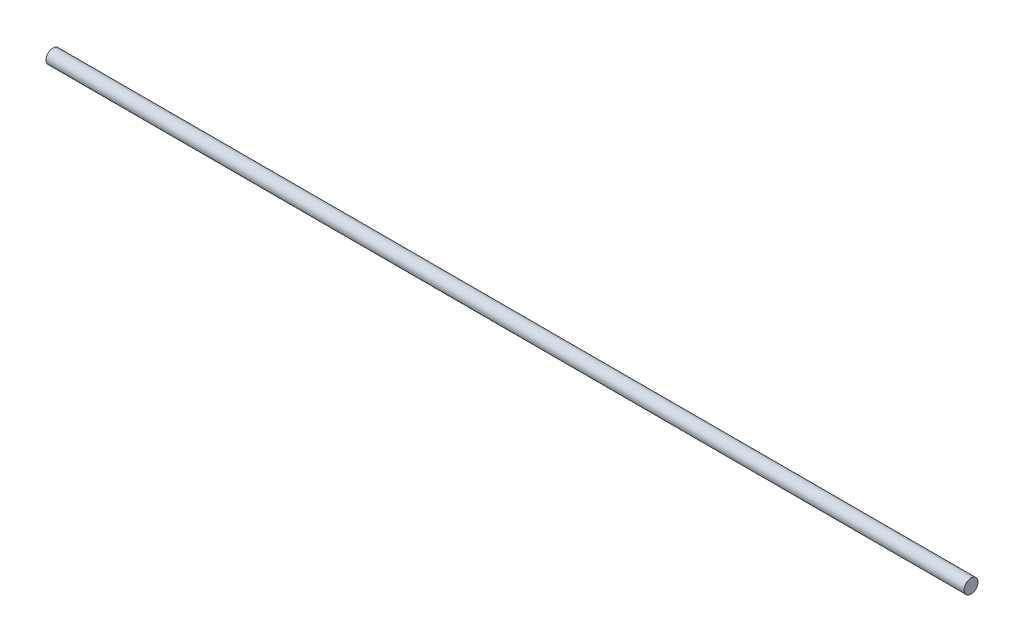
SolidWorks part; units mm, degrees
ref_plane "Front Plane" through (0, 0, 0) normal (0, 0, 1) x (1, 0, 0)
ref_plane "Top Plane" through (0, 0, 0) normal (0, 1, 0) x (1, 0, 0)
ref_plane "Right Plane" through (0, 0, 0) normal (1, 0, 0) x (0, 0, -1)
sketch "Sketch1" plane through (0, 0, 0) normal (1, 0, 0) x (0, 0, -1)
  circle A0 centre (0, 0) radius 3.8
  dimension "D1" = 7.6
extrude "Boss-Extrude1" add sketch "Sketch1" along normal blind 501.65
